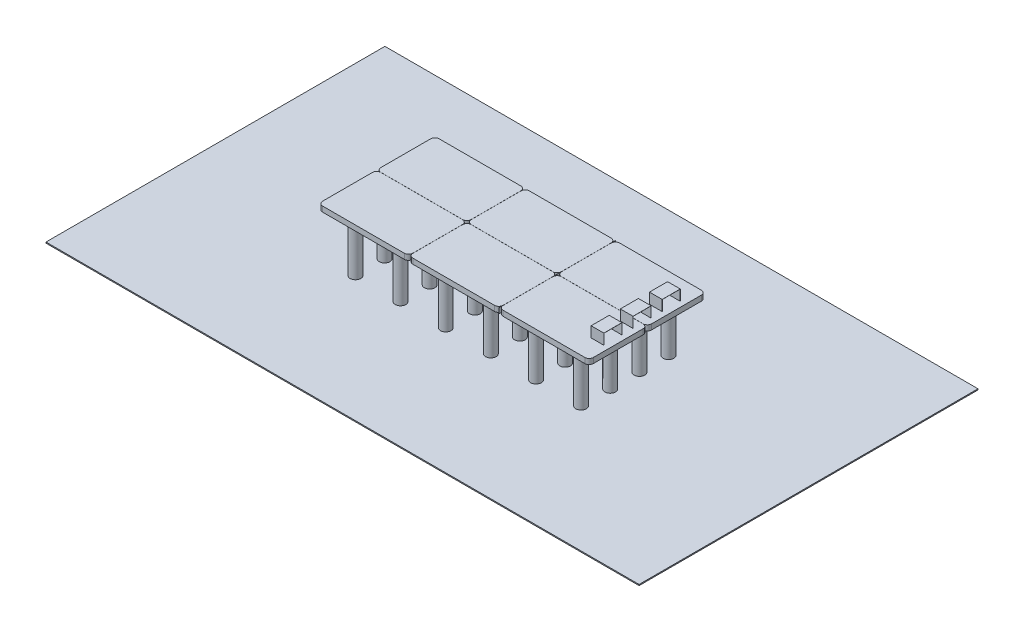
SolidWorks part; units mm, degrees
ref_plane "정면" through (0, 0, 0) normal (0, 0, 1) x (1, 0, 0)
ref_plane "윗면" through (0, 0, 0) normal (0, 1, 0) x (1, 0, 0)
ref_plane "우측면" through (0, 0, 0) normal (1, 0, 0) x (0, 0, -1)
sketch "스케치1" plane through (0, 0, 0) normal (0, 1, 0) x (1, 0, 0)
  line L1 (-1278, 550) -> (1278, 550)
  line L2 (-1278, 550) -> (-1278, -550)
  line L3 (-1278, -550) -> (1278, -550)
  line L4 (1278, 550) -> (1278, -550)
  line L5 (-1278, 550) -> (1278, -550) construction
  line L6 (-1278, -550) -> (1278, 550) construction
  point P0 (0, 0)
  dimension "D1" = 2556
  dimension "D2" = 1100
extrude "보스-돌출1" add sketch "스케치1" along normal blind 50
sketch "스케치2" plane through (0, 0, 0) normal (0, -1, 0) x (1, 0, 0)
  line L0 (-1278, 550) -> (1278, 550) construction
  line L1 (-1278, 550) -> (-426.6667, 550) construction
  line L2 (-426.6667, 550) -> (-425.6667, 550) construction
  line L3 (-426.6667, 550) -> (-426.6667, 0.5)
  line L4 (1278, -550) -> (-1278, -550) construction
  line L5 (-425.6667, 550) -> (-425.6667, 0.5)
  line L6 (-426.6667, -0.5) -> (-426.6667, -550)
  line L9 (-425.6667, 550) -> (425.6667, 550) construction
  line L10 (425.6667, 550) -> (426.6667, 550) construction
  line L11 (425.6667, 550) -> (425.6667, 0.5)
  line L12 (426.6667, 550) -> (426.6667, 0.5)
  line L13 (-426.6667, 550) -> (-425.6667, 550)
  line L14 (425.6667, 550) -> (426.6667, 550)
  line L15 (-426.6667, -550) -> (-425.6667, -550)
  line L16 (425.6667, -550) -> (426.6667, -550)
  line L17 (-1278, -0.5) -> (-426.6667, -0.5)
  line L18 (-1278, 0.5) -> (-426.6667, 0.5)
  line L19 (-1278, -0.5) -> (-1278, 0.5)
  line L20 (1278, -0.5) -> (1278, 0.5)
  line L21 (-425.6667, 0.5) -> (425.6667, 0.5)
  line L22 (-425.6667, -0.5) -> (-425.6667, -550)
  line L23 (-425.6667, -0.5) -> (425.6667, -0.5)
  line L24 (425.6667, -0.5) -> (425.6667, -550)
  line L25 (426.6667, -0.5) -> (426.6667, -550)
  line L26 (426.6667, -0.5) -> (1278, -0.5)
  line L27 (426.6667, 0.5) -> (1278, 0.5)
  line L28 (-1278, 0) -> (1278, 0) construction
  line L29 (-426.1667, 550) -> (-426.1667, -550) construction
  dimension "D1" = 851.3333
  dimension "D2" = 1
  dimension "D3" = 851.3333
  dimension "D4" = 1
extrude "컷-돌출1" cut sketch "스케치2" against normal through all
sketch "스케치3" plane through (0, 0, 0) normal (0, -1, 0) x (1, 0, 0)
  line L0 (-1278, -275.25) -> (1278, -275.25) construction
  line L1 (-1278, -550) -> (-1278, -0.5) construction
  line L2 (1278, -0.5) -> (1278, -550) construction
  line L3 (-852.3333, -550) -> (-852.3333, 550) construction
  line L4 (-426.6667, -550) -> (-1278, -550) construction
  line L5 (-1278, 550) -> (-426.6667, 550) construction
  line L6 (-1278, -275.25) -> (-1278, -0.5) construction
  line L7 (-1278, -137.875) -> (1278, -137.875) construction
  line L8 (-1278, -550) -> (-852.3333, -550) construction
  line L9 (-1065.1667, -550) -> (-1065.1667, -0.5) construction
  line L10 (-1278, -0.5) -> (-426.6667, -0.5) construction
  circle A0 centre (-1065.1667, -137.875) radius 50
  circle A1 centre (-639.5, -137.875) radius 50
  circle A2 centre (-639.5, -412.625) radius 50
  circle A3 centre (-1065.1667, -412.625) radius 50
  circle A4 centre (-212.8333, -137.875) radius 50
  circle A5 centre (212.8333, -137.875) radius 50
  circle A6 centre (-212.8333, -412.625) radius 50
  circle A7 centre (212.8333, -412.625) radius 50
  circle A8 centre (639.5, -137.875) radius 50
  circle A9 centre (1065.1667, -137.875) radius 50
  circle A10 centre (639.5, -412.625) radius 50
  circle A11 centre (1065.1667, -412.625) radius 50
  circle A12 centre (-212.8333, 412.625) radius 50
  circle A13 centre (212.8333, 412.625) radius 50
  circle A14 centre (-212.8333, 137.875) radius 50
  circle A15 centre (212.8333, 137.875) radius 50
  circle A16 centre (639.5, 412.625) radius 50
  circle A17 centre (1065.1667, 412.625) radius 50
  circle A18 centre (639.5, 137.875) radius 50
  circle A19 centre (1065.1667, 137.875) radius 50
  circle A20 centre (-1065.1667, 412.625) radius 50
  circle A21 centre (-639.5, 412.625) radius 50
  circle A22 centre (-1065.1667, 137.875) radius 50
  circle A23 centre (-639.5, 137.875) radius 50
  point P22 (-1065.1667, -137.875)
  dimension "D1" = 100
  dimension "D2" = 3
  dimension "D3" = 2
extrude "보스-돌출2" add sketch "스케치3" along normal blind 500
sketch "스케치4" plane through (0, 50, 0) normal (0, 1, 0) x (1, 0, 0)
  line L0 (-425.67, -40.5) -> (-425.67, -0.5)
  line L1 (-1278, -0.5) -> (-1278, -550) construction
  line L2 (-425.67, -0.5) -> (-385.67, -0.5)
  line L3 (425.6633, -0.5) -> (385.6633, -0.5)
  line L4 (-426.6667, -0.5) -> (-1278, -0.5) construction
  line L5 (425.6633, -40.5) -> (425.6633, -0.5)
  line L6 (-1278, -40.5) -> (-1278, -0.5)
  line L7 (-1278, -0.5) -> (-1238, -0.5)
  line L8 (-426.6667, -0.5) -> (-466.6667, -0.5)
  line L9 (-426.6667, -40.5) -> (-426.6667, -0.5)
  line L10 (-426.6667, -510) -> (-426.6667, -550)
  line L11 (-426.6667, -550) -> (-466.6667, -550)
  line L12 (-1278, -550) -> (-1238, -550)
  line L13 (-1278, -510) -> (-1278, -550)
  line L14 (-1278, 0.5) -> (-1278, -0.5) construction
  line L15 (425.6633, -510) -> (425.6633, -550)
  line L16 (425.6633, -550) -> (385.6633, -550)
  line L17 (-425.67, -550) -> (-385.67, -550)
  line L18 (-425.67, -510) -> (-425.67, -550)
  line L19 (-425.67, 0.5) -> (-425.67, -0.5) construction
  line L20 (-425.67, 510) -> (-425.67, 550)
  line L21 (-425.67, 550) -> (-385.67, 550)
  line L22 (425.6633, 550) -> (385.6633, 550)
  line L23 (425.6633, 510) -> (425.6633, 550)
  line L24 (425.6633, 40.5) -> (425.6633, 0.5)
  line L25 (425.6633, 0.5) -> (385.6633, 0.5)
  line L26 (-425.67, 0.5) -> (-385.67, 0.5)
  line L27 (-425.67, 40.5) -> (-425.67, 0.5)
  line L28 (-425.67, 551) -> (-425.67, 550) construction
  line L29 (-1278, 510) -> (-1278, 550)
  line L30 (-1278, 550) -> (-1238, 550)
  line L31 (-426.6667, 550) -> (-466.6667, 550)
  line L32 (-426.6667, 510) -> (-426.6667, 550)
  line L33 (-426.6667, 40.5) -> (-426.6667, 0.5)
  line L34 (-426.6667, 0.5) -> (-466.6667, 0.5)
  line L35 (-1278, 0.5) -> (-1238, 0.5)
  line L36 (-1278, 40.5) -> (-1278, 0.5)
  line L37 (-1278, 551) -> (-1278, 550) construction
  line L38 (0, 550) -> (0, -550) construction
  line L39 (425.6667, 550) -> (-425.6667, 550) construction
  line L40 (-425.6667, -550) -> (425.6667, -550) construction
  line L41 (1278, 551) -> (1278, 550) construction
  line L42 (425.67, 551) -> (425.67, 550) construction
  line L43 (425.67, 0.5) -> (425.67, -0.5) construction
  line L44 (1278, 0.5) -> (1278, -0.5) construction
  line L45 (1278, 40.5) -> (1278, 0.5)
  line L46 (1278, 0.5) -> (1238, 0.5)
  line L47 (426.6667, 0.5) -> (466.6667, 0.5)
  line L48 (426.6667, 40.5) -> (426.6667, 0.5)
  line L49 (426.6667, 510) -> (426.6667, 550)
  line L50 (426.6667, 550) -> (466.6667, 550)
  line L51 (1278, 550) -> (1238, 550)
  line L52 (1278, 510) -> (1278, 550)
  line L53 (425.67, 40.5) -> (425.67, 0.5)
  line L54 (425.67, 0.5) -> (385.67, 0.5)
  line L55 (425.67, 550) -> (385.67, 550)
  line L56 (425.67, 510) -> (425.67, 550)
  line L57 (425.67, -510) -> (425.67, -550)
  line L58 (425.67, -550) -> (385.67, -550)
  line L59 (1278, -510) -> (1278, -550)
  line L60 (1278, -550) -> (1238, -550)
  line L61 (426.6667, -550) -> (466.6667, -550)
  line L62 (426.6667, -510) -> (426.6667, -550)
  line L63 (426.6667, -40.5) -> (426.6667, -0.5)
  line L64 (426.6667, -0.5) -> (466.6667, -0.5)
  line L65 (1278, -0.5) -> (1238, -0.5)
  line L66 (1278, -40.5) -> (1278, -0.5)
  line L67 (425.67, -0.5) -> (385.67, -0.5)
  line L68 (425.67, -40.5) -> (425.67, -0.5)
  arc A0 (-1238, -0.5) -> (-1278, -40.5) centre (-1238, -40.5) ccw
  arc A1 (-466.6667, -0.5) -> (-426.6667, -40.5) centre (-466.6667, -40.5) cw
  arc A2 (-466.6667, -550) -> (-426.6667, -510) centre (-466.6667, -510) ccw
  arc A3 (-1238, -550) -> (-1278, -510) centre (-1238, -510) cw
  arc A4 (-385.67, -0.5) -> (-425.67, -40.5) centre (-385.67, -40.5) ccw
  arc A5 (385.6633, -0.5) -> (425.6633, -40.5) centre (385.6633, -40.5) cw
  arc A6 (385.6633, -550) -> (425.6633, -510) centre (385.6633, -510) ccw
  arc A7 (-385.67, -550) -> (-425.67, -510) centre (-385.67, -510) cw
  arc A8 (-385.67, 550) -> (-425.67, 510) centre (-385.67, 510) ccw
  arc A9 (385.6633, 550) -> (425.6633, 510) centre (385.6633, 510) cw
  arc A10 (385.6633, 0.5) -> (425.6633, 40.5) centre (385.6633, 40.5) ccw
  arc A11 (-385.67, 0.5) -> (-425.67, 40.5) centre (-385.67, 40.5) cw
  arc A12 (-1238, 550) -> (-1278, 510) centre (-1238, 510) ccw
  arc A13 (-466.6667, 550) -> (-426.6667, 510) centre (-466.6667, 510) cw
  arc A14 (-466.6667, 0.5) -> (-426.6667, 40.5) centre (-466.6667, 40.5) ccw
  arc A15 (-1238, 0.5) -> (-1278, 40.5) centre (-1238, 40.5) cw
  arc A16 (1238, 0.5) -> (1278, 40.5) centre (1238, 40.5) ccw
  arc A17 (466.6667, 0.5) -> (426.6667, 40.5) centre (466.6667, 40.5) cw
  arc A18 (466.6667, 550) -> (426.6667, 510) centre (466.6667, 510) ccw
  arc A19 (1238, 550) -> (1278, 510) centre (1238, 510) cw
  arc A20 (385.67, 0.5) -> (425.67, 40.5) centre (385.67, 40.5) ccw
  arc A21 (385.67, 550) -> (425.67, 510) centre (385.67, 510) cw
  arc A22 (385.67, -550) -> (425.67, -510) centre (385.67, -510) ccw
  arc A23 (385.67, -0.5) -> (425.67, -40.5) centre (385.67, -40.5) cw
  arc A24 (1238, -550) -> (1278, -510) centre (1238, -510) ccw
  arc A25 (466.6667, -550) -> (426.6667, -510) centre (466.6667, -510) cw
  arc A26 (466.6667, -0.5) -> (426.6667, -40.5) centre (466.6667, -40.5) ccw
  arc A27 (1238, -0.5) -> (1278, -40.5) centre (1238, -40.5) cw
  line M2 (-426.6667, -0.5) -> (-1278, -0.5)
  line M3 (-1278, -0.5) -> (-1278, -550)
  line M4 (-1278, -550) -> (-426.6667, -550)
  line M5 (-426.6667, -550) -> (-426.6667, -0.5)
  dimension "D1" = 80
  dimension "D2" = 851.3333
  dimension "D3" = 549.5
  dimension "D4" = 2
  dimension "D5" = 2
extrude "컷-돌출3" cut sketch "스케치4" against normal through all contours A8 L21 L20 | A18 L50 L49 | L22 A21 L23 | L31 A13 L32 | A12 L30 L29 | L51 A19 L52 | A0 M2 M3 | L35 A15 L36 | A1 M2 M5 | A14 L34 L33 | L26 A11 L27 | A4 L2 L0 | A20 L25 L24 | L47 A17 L48 | A26 L64 L63 | L3 A23 L5 | A16 L46 L45 | L65 A27 L66 | A24 L60 L59 | L61 A25 L62 | A22 L16 L15 | A2 M4 M5 | L17 A7 L18 | A3 M4 M3
sketch "스케치5" plane through (0, -500, 0) normal (0, -1, 0) x (1, 0, 0)
  line L1 (-2800, 1600) -> (2800, 1600)
  line L2 (-2800, 1600) -> (-2800, -1600)
  line L3 (-2800, -1600) -> (2800, -1600)
  line L4 (2800, 1600) -> (2800, -1600)
  line L5 (-2800, 1600) -> (2800, -1600) construction
  line L6 (-2800, -1600) -> (2800, 1600) construction
  point P0 (0, 0)
  dimension "D1" = 5600
  dimension "D2" = 3200
extrude "보스-돌출3" add sketch "스케치5" along normal blind 10
sketch "스케치6" plane through (0, 50, 0) normal (0, 1, 0) x (1, 0, 0)
  line L0 (1108, 550) -> (1108, -550) construction
  line L1 (1238, 550) -> (466.6667, 550) construction
  line L2 (466.6667, -550) -> (1238, -550) construction
  line L3 (1228, 550) -> (1228, -550) construction
  line L4 (1278, 40.5) -> (1278, 510) construction
  line L5 (1278, 275.25) -> (-1278, 275.25) construction
  line L6 (-1278, 510) -> (-1278, 40.5) construction
  line L7 (1278, 0) -> (-1278, 0) construction
  line L8 (1278, -275.25) -> (-1278, -275.25) construction
  line L9 (1278, -510) -> (1278, -40.5) construction
  line L10 (-1278, -40.5) -> (-1278, -510) construction
  line L12 (1228, 360.67) -> (1108, 360.67)
  line L13 (1228, 189.83) -> (1108, 189.83)
  line L14 (1228, 360.67) -> (1228, 189.83)
  line L15 (1108, 360.67) -> (1108, 189.83)
  line L16 (1228, -189.83) -> (1108, -189.83)
  line L17 (1228, -360.67) -> (1228, -189.83)
  line L18 (1228, -360.67) -> (1108, -360.67)
  line L19 (1108, -360.67) -> (1108, -189.83)
  line L21 (1108, -85.42) -> (1228, -85.42)
  line L22 (1108, 85.42) -> (1228, 85.42)
  line L23 (1108, -85.42) -> (1108, 85.42)
  line L24 (1228, -85.42) -> (1228, 85.42)
  point P23 (1228, 275.25)
  point P25 (1108, 275.25)
  point P33 (1108, 0)
  point P35 (1228, 0)
  dimension "D1" = 50
  dimension "D2" = 120
  dimension "D3" = 1100
  dimension "D4" = 189.33
extrude "보스-돌출4" add sketch "스케치6" along normal blind 99.6
sketch "스케치7" plane through (1108, 0, 0) normal (-1, 0, 0) x (0, 0, 1)
  line L0 (-510, 50) -> (-40.5, 50) construction
  line L1 (-359.67, 50) -> (-190.83, 50)
  line L2 (-359.67, 50) -> (-359.67, 148.6)
  line L3 (-359.67, 148.6) -> (-190.83, 148.6)
  line L4 (-190.83, 50) -> (-190.83, 148.6)
  line L5 (-360.67, 149.6) -> (-360.67, 50) construction
  line L6 (-360.67, 149.6) -> (-189.83, 149.6) construction
  line L7 (-189.83, 149.6) -> (-189.83, 50) construction
  line L8 (-85.42, 149.6) -> (-85.42, 50) construction
  line L9 (-84.42, 50) -> (84.42, 50)
  line L10 (-84.42, 50) -> (-84.42, 148.6)
  line L11 (-84.42, 148.6) -> (84.42, 148.6)
  line L12 (84.42, 50) -> (84.42, 148.6)
  line L13 (-85.42, 149.6) -> (85.42, 149.6) construction
  line L14 (85.42, 149.6) -> (85.42, 50) construction
  line L15 (189.83, 50) -> (360.67, 50) construction
  line L16 (190.83, 50) -> (359.67, 50)
  line L17 (190.83, 50) -> (190.83, 148.6)
  line L18 (190.83, 148.6) -> (359.67, 148.6)
  line L19 (359.67, 50) -> (359.67, 148.6)
  line L20 (189.83, 149.6) -> (189.83, 50) construction
  line L21 (189.83, 149.6) -> (360.67, 149.6) construction
  line L22 (360.67, 149.6) -> (360.67, 50) construction
  dimension "D1" = 1
  dimension "D2" = 1
  dimension "D3" = 1
  dimension "D4" = 1
  dimension "D5" = 1
  dimension "D6" = 1
  dimension "D7" = 1
  dimension "D8" = 1
  dimension "D9" = 1
extrude "컷-돌출4" cut sketch "스케치7" against normal blind 139.6
